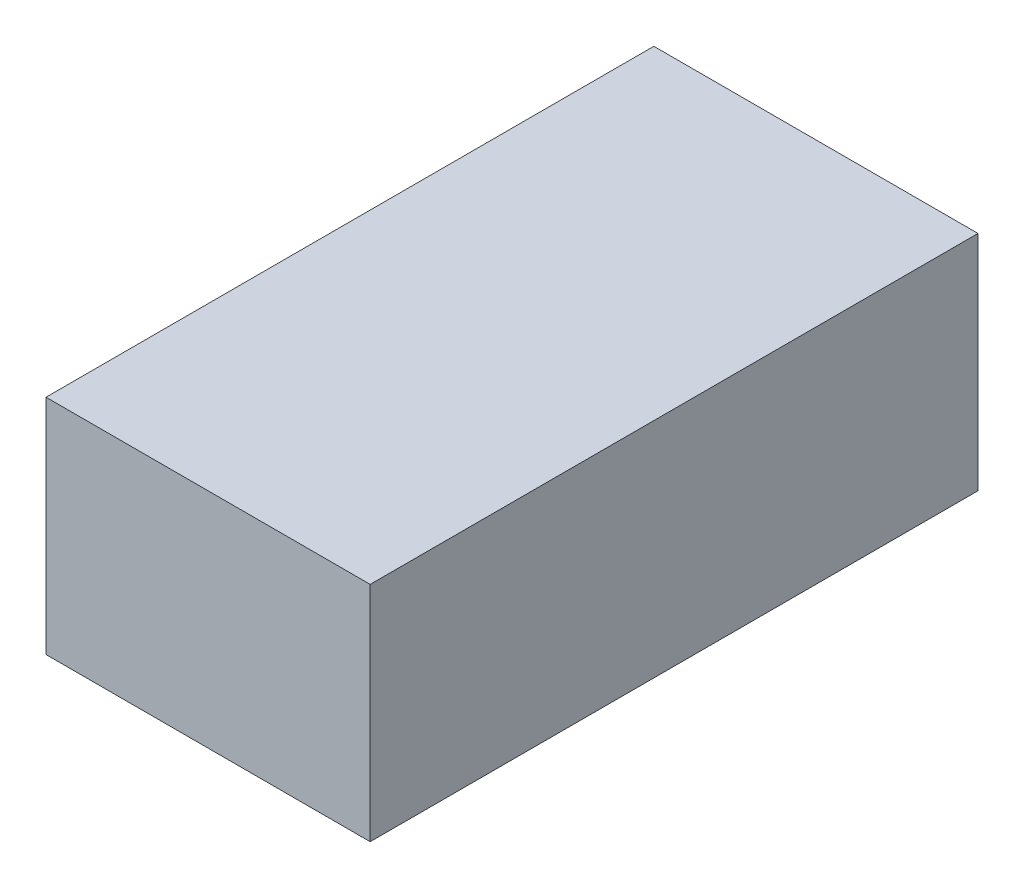
SolidWorks part; units mm, degrees
ref_plane "前视基准面" through (0, 0, 0) normal (0, 0, 1) x (1, 0, 0)
ref_plane "上视基准面" through (0, 0, 0) normal (0, 1, 0) x (1, 0, 0)
ref_plane "右视基准面" through (0, 0, 0) normal (1, 0, 0) x (0, 0, -1)
sketch "草图1" plane through (0, 0, 0) normal (0, 0, 1) x (1, 0, 0)
  line L1 (0, 0) -> (80, 0)
  line L2 (0, 0) -> (0, 55)
  line L3 (0, 55) -> (80, 55)
  line L4 (80, 0) -> (80, 55)
  dimension "D1" = 80
  dimension "D2" = 55
extrude "凸台-拉伸1" add sketch "草图1" along normal blind 150
